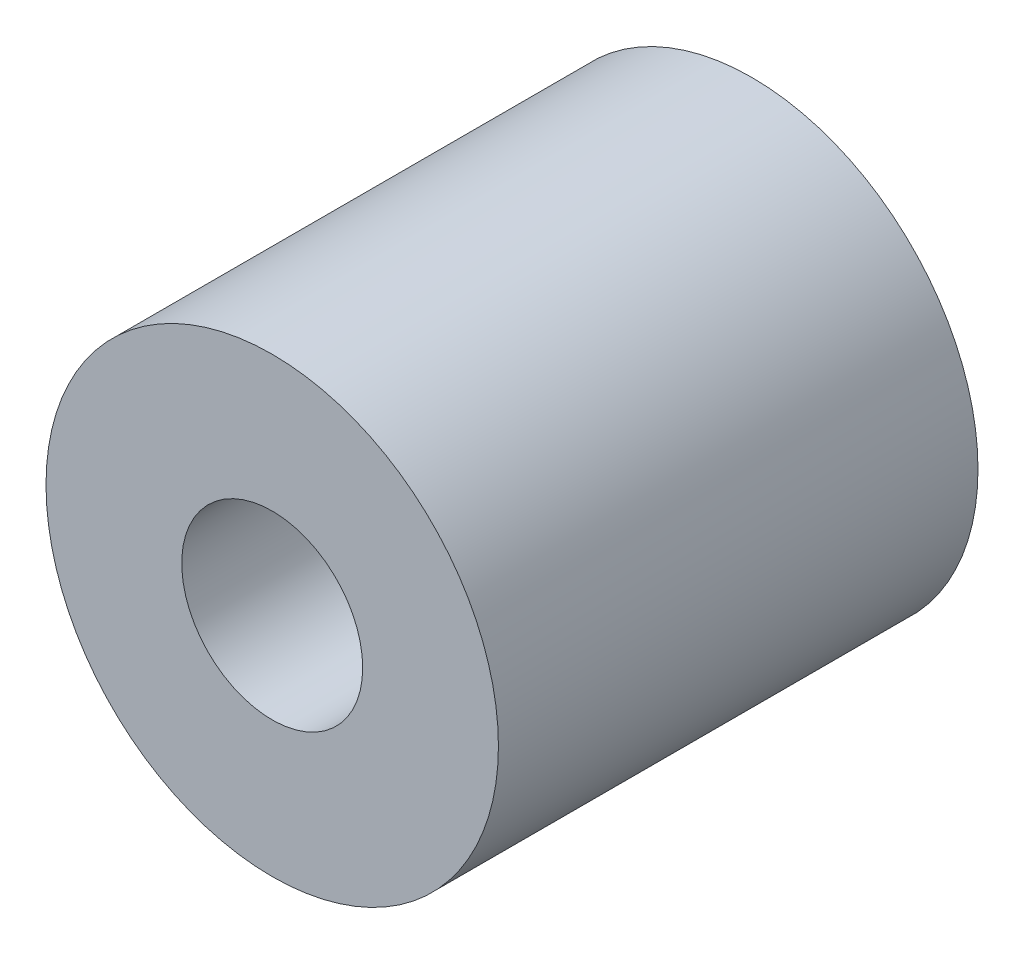
SolidWorks part; units mm, degrees
material "6061 Alloy"
ref_plane "Front Plane" through (0, 0, 0) normal (0, 0, 1) x (1, 0, 0)
ref_plane "Top Plane" through (0, 0, 0) normal (0, 1, 0) x (1, 0, 0)
ref_plane "Right Plane" through (0, 0, 0) normal (1, 0, 0) x (0, 0, -1)
sketch "Sketch1" plane through (0, 0, 0) normal (0, 0, 1) x (1, 0, 0)
  circle A0 centre (0, 0) radius 7.5
extrude "Boss-Extrude1" add sketch "Sketch1" along normal blind 15.9
sketch "Sketch2" plane through (0, 0, 15.9) normal (0, 0, 1) x (1, 0, 0)
  circle A0 centre (0, 0) radius 3
extrude "Cut-Extrude1" cut sketch "Sketch2" against normal blind 7.5
sketch "Sketch4" plane through (0, 0, 0) normal (0, 0, -1) x (-1, 0, 0)
  circle A0 centre (0, 0) radius 3
extrude "Cut-Extrude2" cut sketch "Sketch4" against normal blind 7.5
